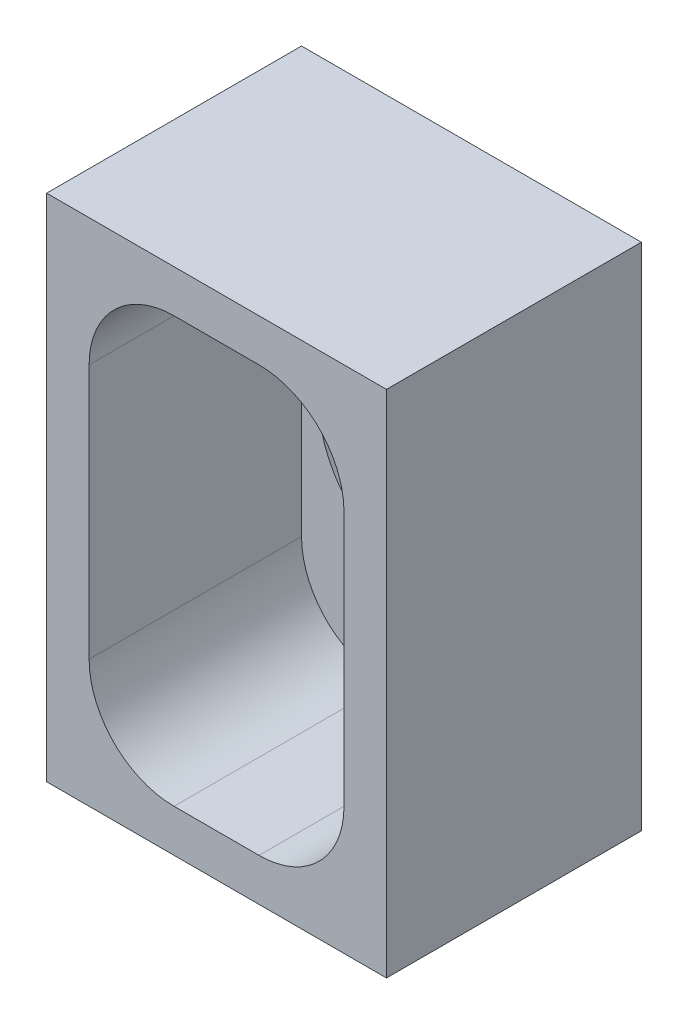
SolidWorks part; units mm, degrees
material "ABS"
ref_plane "正面" through (0, 0, 0) normal (0, 0, 1) x (1, 0, 0)
ref_plane "平面" through (0, 0, 0) normal (0, 1, 0) x (1, 0, 0)
ref_plane "右側面" through (0, 0, 0) normal (1, 0, 0) x (0, 0, -1)
sketch "ｽｹｯﾁ1" plane through (0, 0, 0) normal (0, 0, 1) x (1, 0, 0)
  line L1 (-20, 25) -> (20, 25)
  line L2 (-20, 25) -> (-20, -25)
  line L3 (-20, -25) -> (20, -25)
  line L4 (20, 25) -> (20, -25)
  line L5 (-20, 25) -> (20, -25) construction
  line L6 (-20, -25) -> (20, 25) construction
  circle A0 centre (0, 0) radius 8.5 construction
  circle A1 centre (0, 8.5) radius 1.6
  circle A2 centre (8.5, 0) radius 1.6
  circle A3 centre (0, -8.5) radius 1.6
  circle A4 centre (-8.5, 0) radius 1.6
  circle A5 centre (0, 0) radius 3.25
  point P0 (0, 0)
  point P19 (0, 0)
  dimension "D2" = 17
  dimension "D3" = 3.2
  dimension "D6" = 6.5
  dimension "D1" = 50
  dimension "D5" = 40
  dimension "D4" = 4
extrude "ﾎﾞｽ - 押し出し1" add sketch "ｽｹｯﾁ1" along normal blind 5
sketch "ｽｹｯﾁ2" plane through (0, 0, 5) normal (0, 0, 1) x (1, 0, 0)
  circle A0 centre (0, 0) radius 13
  dimension "D1" = 26
extrude "ｶｯﾄ - 押し出し1" cut sketch "ｽｹｯﾁ2" against normal blind 2.5
sketch "ｽｹｯﾁ3" plane through (0, 0, 0) normal (0, 0, -1) x (-1, 0, 0)
  line L0 (20, 25) -> (20, -25) construction
  line L1 (-20, 25) -> (20, 25)
  line L2 (-20, 25) -> (-20, 30)
  line L3 (-20, 30) -> (20, 30)
  line L4 (20, 25) -> (20, 30)
  line L6 (-20, -25) -> (20, -25)
  line L7 (-20, -25) -> (-20, -30)
  line L8 (-20, -30) -> (20, -30)
  line L9 (20, -25) -> (20, -30)
  dimension "D1" = 5
extrude "ﾎﾞｽ - 押し出し2" add sketch "ｽｹｯﾁ3" against normal blind 30
sketch "ｽｹｯﾁ4" plane through (20, 0, 0) normal (1, 0, 0) x (0, 0, -1)
  line L0 (-30, -25) -> (-5, -25) construction
  line L1 (-5, 25) -> (-30, 25)
  line L2 (-5, 25) -> (-5, -25)
  line L3 (-5, -25) -> (-30, -25)
  line L4 (-30, 25) -> (-30, -25)
  line L5 (-30, 30) -> (-30, 25) construction
extrude "ﾎﾞｽ - 押し出し3" add sketch "ｽｹｯﾁ4" against normal blind 5
mirror "ﾐﾗｰ1" about plane through (0, 0, 0) normal (1, 0, 0) of "ﾎﾞｽ - 押し出し3"
fillet "ﾌｨﾚｯﾄ1" radius 10 4 edges at (-15, -25, 17.5) (15, -25, 17.5) (15, 25, 17.5) (-15, 25, 17.5)
